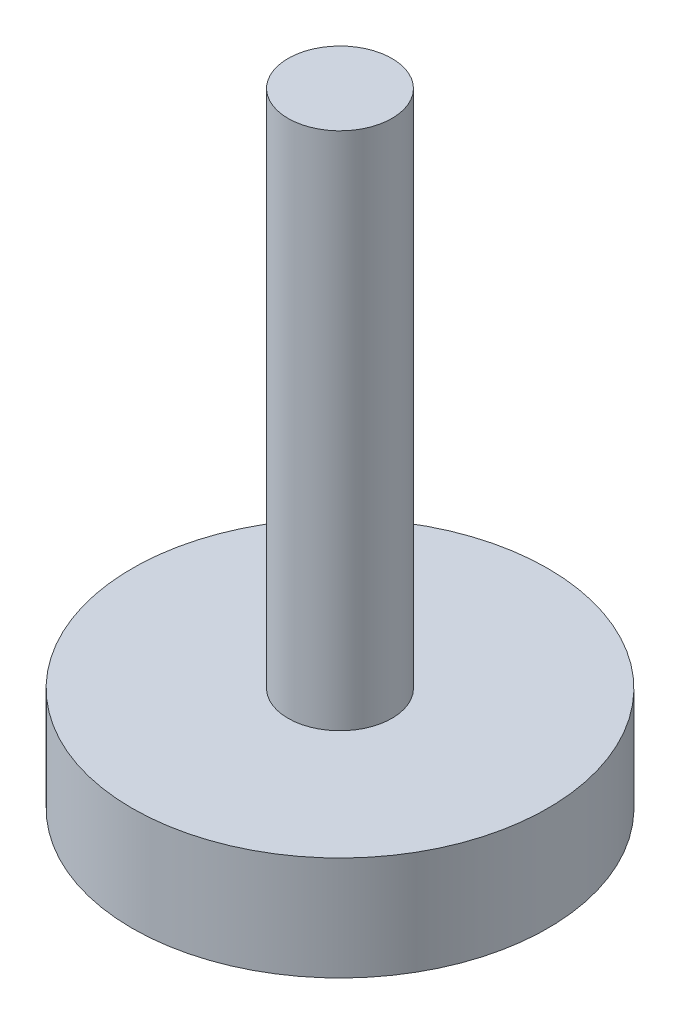
SolidWorks part; units mm, degrees
ref_plane "Front" through (0, 0, 0) normal (0, 0, 1) x (1, 0, 0)
ref_plane "Top" through (0, 0, 0) normal (0, 1, 0) x (1, 0, 0)
ref_plane "Right" through (0, 0, 0) normal (1, 0, 0) x (0, 0, -1)
sketch "Skizze1" plane through (0, 0, 0) normal (0, 1, 0) x (1, 0, 0)
  circle A0 centre (0, 0) radius 20
  dimension "D1" = 40
extrude "Aufsatz-Linear austragen1" add sketch "Skizze1" along normal blind 10
sketch "Skizze2" plane through (0, 10, 0) normal (0, 1, 0) x (1, 0, 0)
  circle A0 centre (0, 0) radius 5
  dimension "D1" = 10
extrude "Aufsatz-Linear austragen2" add sketch "Skizze2" along normal blind 50
cosmetic thread "Gewindedarstellung1" parameters "D2"=9
